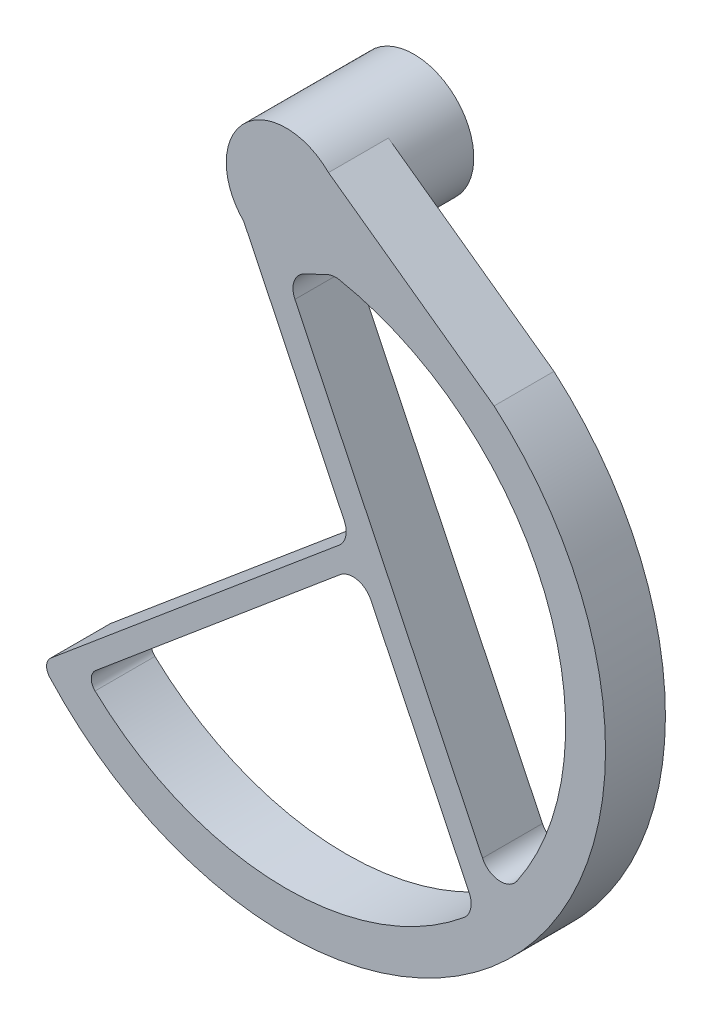
SolidWorks part; units mm, degrees
ref_plane "正面" through (0, 0, 0) normal (0, 0, 1) x (1, 0, 0)
ref_plane "平面" through (0, 0, 0) normal (0, 1, 0) x (1, 0, 0)
ref_plane "右側面" through (0, 0, 0) normal (1, 0, 0) x (0, 0, -1)
sketch "ｽｹｯﾁ4" plane through (0, 0, 0) normal (0, 0, 1) x (1, 0, 0)
  line L0 (0, 0.7897) -> (0, 0)
  line L1 (-53.6231, -124.9951) -> (-58.9406, -129.4571)
  line L3 (-10.6066, -10.6066) -> (14.5363, -62.8896)
  line L4 (-53.6231, -124.9951) -> (13.2442, -68.8868)
  line L5 (21.2324, -76.8138) -> (45.8448, -127.9938)
  line L6 (10.6066, 10.6066) -> (52.0762, -19.2705)
  line L7 (-58.0696, -135.2532) -> (-57.9498, -135.1527)
  line L8 (-47.7477, -126.5866) -> (13.5112, -75.1515)
  arc A1 (-59.2335, -133.7716) -> (52.0762, -19.2705) centre (0, -80) ccw
  arc A2 (-47.8702, -131.073) -> (44.5187, -134.0193) centre (0, -80) ccw
  arc A3 (10.6066, 10.6066) -> (-10.6066, -10.6066) centre (0, 0) ccw
  arc A4 (-59.2335, -133.7716) -> (-58.9406, -129.4571) centre (-57.0123, -131.7552) cw
  arc A5 (-47.8702, -131.073) -> (-47.7477, -126.5866) centre (-45.8186, -128.8841) cw
  arc A6 (13.5112, -75.1515) -> (21.2324, -76.8138) centre (16.7264, -78.9807) cw
  arc A7 (13.2442, -68.8868) -> (14.5363, -62.8896) centre (10.0302, -65.0566) ccw
  arc A8 (45.8448, -127.9938) -> (44.5187, -134.0193) centre (41.3388, -130.1608) cw
  point P18 (-61.2836, -131.423)
  point P21 (-50.2744, -128.7081)
  point P24 (18.4421, -71.0114)
  dimension "D3" = 140
  dimension "D4" = 30
  dimension "D5" = 5
  dimension "D6" = 3
  dimension "D7" = 3
  dimension "D8" = 5
  dimension "D9" = 5
  dimension "D10" = 5
  dimension "D2" = 5
extrude "ﾎﾞｽ - 押し出し1" add sketch "ｽｹｯﾁ4" along normal blind 15
sketch "ｽｹｯﾁ6" plane through (0, 0, 15) normal (0, 0, 1) x (1, 0, 0)
  line L6 (49.1896, -118.7973) -> (2.2018, -21.089)
  line L7 (6.4834, -13.4819) -> (4.5408, -14.416)
  line L8 (6.4834, -13.4819) -> (10.2197, -11.6851)
  arc A0 (57.8261, -119.448) -> (13.3394, -11.2828) centre (0, -80) ccw
  arc A1 (2.2018, -21.089) -> (4.5408, -14.416) centre (6.7078, -18.9221) cw
  arc A2 (13.3394, -11.2828) -> (10.2197, -11.6851) centre (12.3866, -16.1911) ccw
  arc A3 (57.8261, -119.448) -> (49.1896, -118.7973) centre (53.6956, -116.6303) cw
  point P7 (0.0348, -16.583)
  point P14 (52.6925, -126.0814)
  dimension "D3" = 121.502
  dimension "D4" = 70
  dimension "D1" = 5
  dimension "D2" = 5
  dimension "D5" = 5
  dimension "D6" = 90
extrude "ｶｯﾄ - 押し出し1" cut sketch "ｽｹｯﾁ6" against normal blind 15
sketch "ｽｹｯﾁ11" plane through (0, 0, 0) normal (0, 0, -1) x (-1, 0, 0)
  circle A0 centre (0, 0) radius 15
extrude "ﾎﾞｽ - 押し出し3" add sketch "ｽｹｯﾁ11" along normal blind 17
sketch "ｽｹｯﾁ12" plane through (0, 0, -17) normal (0, 0, -1) x (-1, 0, 0)
  circle A0 centre (0, 0) radius 10
extrude "ｶｯﾄ - 押し出し5" cut sketch "ｽｹｯﾁ12" against normal blind 2
